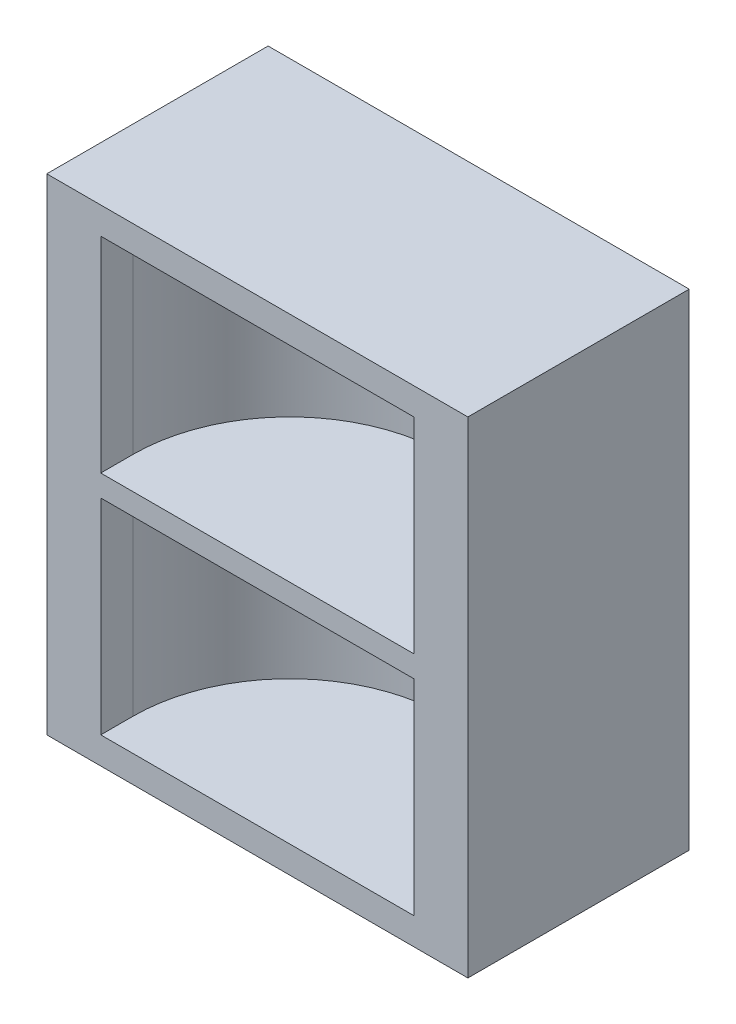
SolidWorks part; units mm, degrees
ref_plane "Front Plane" through (0, 0, 0) normal (1, 0, 0) x (0, 1, 0)
ref_plane "Top Plane" through (0, 0, 0) normal (0, 0, 1) x (0, 1, 0)
ref_plane "Right Plane" through (0, 0, 0) normal (0, 1, 0) x (-1, 0, 0)
sketch "Sketch1" plane through (0, 0, 0) normal (0, 1, 0) x (-1, 0, 0)
  line L0 (29, 0) -> (83.0362, 0) construction
  line L1 (0, 0) -> (0, 56.0328) construction
  line L2 (39, 0) -> (29, 0)
  line L4 (-39, -35) -> (39, -35)
  line L6 (-29, 0) -> (-39, 0)
  line L7 (-39, 0) -> (-39, -35)
  line L8 (39, 0) -> (39, -35)
  line L9 (-29, 0) -> (29, 0)
  arc A0 (-29, 0) -> (29, 0) centre (0, 0) ccw construction
  dimension "D1" = 58
  dimension "D2" = 10
  dimension "D3" = 35
  dimension "D4" = 90
extrude "Boss-Extrude1" add sketch "Sketch1" along normal mid plane 90
sketch "Sketch2" plane through (0, 0, 0) normal (0, 0, 1) x (1, 0, 0)
  line L0 (0, 45) -> (0, -45) construction
  line L1 (-39, 45) -> (39, 45) construction
  line L2 (-39, -45) -> (39, -45) construction
  line L3 (0, 0) -> (-66.2487, 0) construction
  line L8 (0, -2) -> (-29, -2)
  line L9 (0, 40) -> (-29, 40)
  line L14 (0, 40) -> (0, 2)
  line L15 (0, 2) -> (-29, 2)
  line L16 (-29, 40) -> (-29, 2)
  line L17 (-29, -40) -> (-29, -2)
  line L18 (0, -40) -> (-29, -40)
  line L19 (0, -40) -> (0, -2)
  dimension "D1" = 29
  dimension "D2" = 5
  dimension "D3" = 2
revolve "Cut-Revolve4" cut sketch "Sketch2" angle 360 about L0
sketch "Sketch3" plane through (0, 0, 0) normal (0, 0, 1) x (1, 0, 0)
  line L0 (-29, -40) -> (-29, -2) construction
  line L1 (29, -40) -> (-29, -40) construction
  line L2 (29, -2) -> (29, -40) construction
  line L3 (-29, -2) -> (29, -2) construction
  line L4 (-39, -45) -> (39, -45)
  line L5 (39, -45) -> (39, 45)
  line L6 (39, 45) -> (-39, 45)
  line L7 (-39, 45) -> (-39, -45)
  line L8 (-39, -45) -> (39, -45)
  line L9 (39, -45) -> (39, 45)
  line L10 (39, 45) -> (-39, 45)
  line L11 (-39, 45) -> (-39, -45)
  line L12 (29, 2) -> (-29, 2) construction
  line L13 (29, 40) -> (29, 2) construction
  line L14 (-29, 40) -> (29, 40) construction
  line L15 (-29, 2) -> (-29, 40) construction
  line L16 (-29, -40) -> (-29, -2)
  line L17 (29, -40) -> (-29, -40)
  line L18 (29, -2) -> (29, -40)
  line L19 (-29, -2) -> (29, -2)
  line L20 (29, 2) -> (-29, 2)
  line L21 (29, 40) -> (29, 2)
  line L22 (-29, 40) -> (29, 40)
  line L23 (-29, 2) -> (-29, 40)
  dimension "D1" = 0
extrude "Boss-Extrude2" add sketch "Sketch3" along normal blind 6
